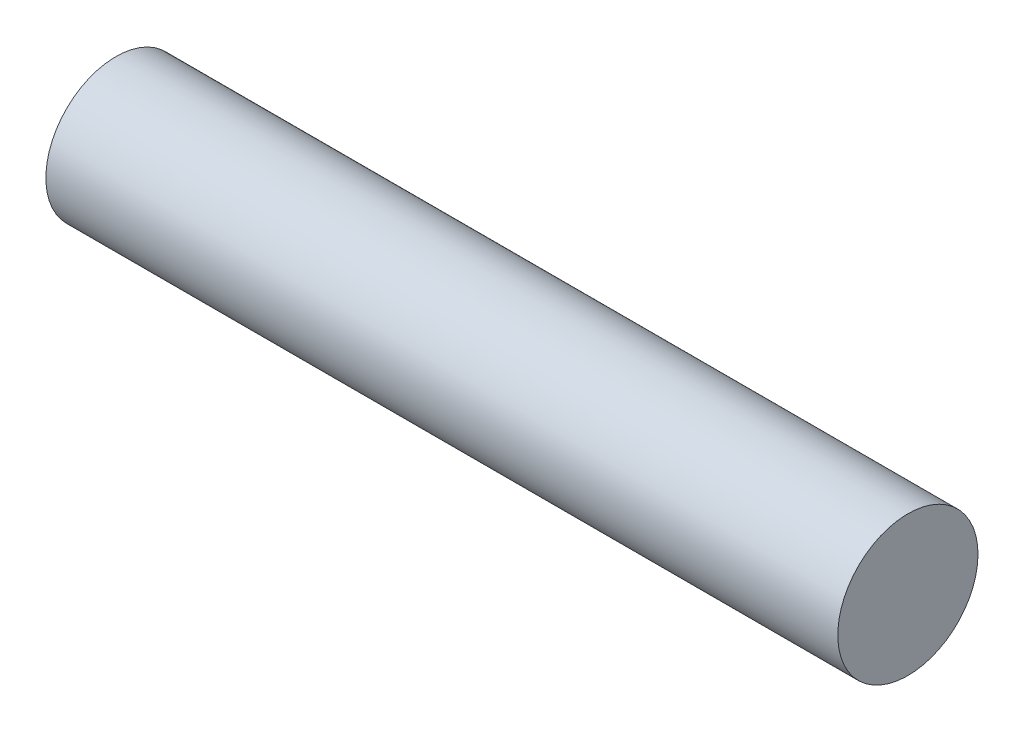
SolidWorks part; units mm, degrees
ref_plane "Front Plane" through (0, 0, 0) normal (1, 0, 0) x (0, 1, 0)
ref_plane "Top Plane" through (0, 0, 0) normal (0, 0, 1) x (0, 1, 0)
ref_plane "Right Plane" through (0, 0, 0) normal (0, 1, 0) x (-1, 0, 0)
sketch "Sketch1" plane through (0, 0, 0) normal (1, 0, 0) x (0, 1, 0)
  circle A0 centre (0, 0) radius 12.5
  dimension "D1" = 25
extrude "Boss-Extrude1" add sketch "Sketch1" along normal blind 141.2
